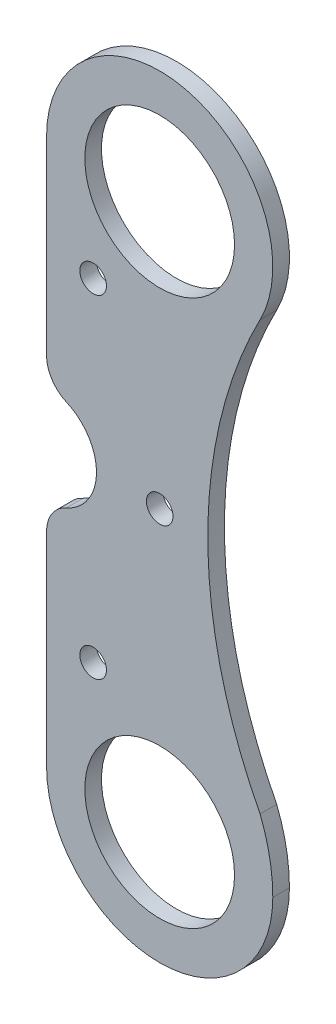
SolidWorks part; units mm, degrees
material "6061 Alloy"
ref_plane "Front Plane" through (0, 0, 0) normal (0, 0, 1) x (1, 0, 0)
ref_plane "Top Plane" through (0, 0, 0) normal (0, 1, 0) x (1, 0, 0)
ref_plane "Right Plane" through (0, 0, 0) normal (1, 0, 0) x (0, 0, -1)
sketch "Sketch1" plane through (0, 0, 0) normal (0, 0, 1) x (1, 0, 0)
  line L0 (0, 0) -> (0, -101.6) construction
  line L1 (21.59, -120.5575) -> (-21.59, -120.5575) construction
  line L2 (-8.89, 25.4) -> (8.89, 25.4)
  line L3 (-21.59, 12.7) -> (-21.59, -117.7751)
  line L5 (21.59, 12.7) -> (21.59, -117.7751)
  line L9 (-23.3829, -122.6853) -> (-33.2033, -134.3394)
  line L10 (-36.322, 25.4) -> (20.828, 25.4) construction
  line L11 (-36.322, 25.4) -> (-36.322, -203.2) construction
  line L12 (-36.322, -203.2) -> (20.828, -203.2) construction
  line L13 (20.828, 25.4) -> (20.828, -203.2) construction
  line L15 (-7.9527, -155.6168) -> (19.7971, -122.6853)
  line L16 (-32.4392, -143.2871) -> (-16.9004, -156.3809)
  circle A0 centre (0, 0) radius 38.1 construction
  circle A1 centre (0, -101.6) radius 38.1 construction
  circle A2 centre (0, 0) radius 14.2875
  circle A3 centre (0, -101.6) radius 14.2875
  arc A6 (8.89, 25.4) -> (21.59, 12.7) centre (8.89, 12.7) cw
  arc A7 (-8.89, 25.4) -> (-21.59, 12.7) centre (-8.89, 12.7) ccw
  circle A10 centre (-18.5321, -142.5501) radius 2.54
  arc A13 (-23.3829, -122.6853) -> (-21.59, -117.7751) centre (-29.21, -117.7751) ccw
  arc A14 (19.7971, -122.6853) -> (21.59, -117.7751) centre (13.97, -117.7751) ccw
  arc A15 (-16.9004, -156.3809) -> (-7.9527, -155.6168) centre (-12.8086, -151.525) ccw
  arc A16 (-33.2033, -134.3394) -> (-32.4392, -143.2871) centre (-28.3474, -138.4312) ccw
  circle A17 centre (0, -50.8) radius 2.54
  point P13 (-192.705, 39.2708)
  point P20 (21.59, 25.4)
  point P23 (-21.59, 25.4)
  point P31 (-36.322, -138.0404)
  dimension "D2" = 76.2
  dimension "D3" = 76.2
  dimension "D4" = 28.575
  dimension "D5" = 28.575
  dimension "D10" = 228.6
  dimension "D11" = 36.322
  dimension "D13" = 5.08
  dimension "D19" = 6.35
  dimension "D20" = 7.62
  dimension "D21" = 12.7
  dimension "D22" = 5.08
  dimension "D1" = 101.6
  dimension "D6" = 43.18
  dimension "D7" = 21.59
  dimension "D8" = 25.4
  dimension "D9" = 57.15
  dimension "D12" = 25.4
  dimension "D14" = 33.02
  dimension "D15" = 16.51
  dimension "D16" = 21.59
  dimension "D17" = 9.525
  dimension "D18" = 18.9575
extrude "Boss-Extrude1" add sketch "Sketch1" along normal blind 3.175
sketch "Sketch2" plane through (0, 0, 0) normal (0, 0, 1) x (1, 0, 0)
  line L0 (-21.59, -41.275) -> (-21.59, -60.325)
  line L1 (0, 0) -> (0, -101.6) construction
  line L4 (21.59, -117.7751) -> (21.59, 12.7) construction
  line L5 (-21.59, -50.8) -> (97.79, -50.8) construction
  line L6 (-21.59, 12.7) -> (-21.59, -117.7751) construction
  line L7 (0, 0) -> (-39.9512, 0) construction
  line L9 (16.51, -115.5122) -> (-17.5013, -155.8745)
  line L10 (-32.4392, -143.2871) -> (-16.9004, -156.3809) construction
  line L11 (-7.9527, -155.6168) -> (19.7971, -122.6853) construction
  line L13 (27.94, -121.6567) -> (-7.6203, -163.8572)
  line L14 (-7.6203, -163.8572) -> (-17.5013, -155.8745)
  line L15 (27.94, -121.6567) -> (27.94, 0)
  line L16 (27.94, 0) -> (21.59, 0)
  arc A1 (19.1591, -91.6472) -> (19.1591, -9.9528) centre (97.79, -50.8) cw
  arc A2 (-21.59, -60.325) -> (-21.59, -41.275) centre (-21.59, -50.8) ccw
  arc A3 (21.59, 0) -> (19.1591, -9.9528) centre (0, 0) cw
  arc A4 (21.59, -101.6) -> (19.1591, -91.6472) centre (0, -101.6) ccw
  arc A5 (21.59, -101.6) -> (16.51, -115.5122) centre (0, -101.6) cw
  dimension "D2" = 12.7
  dimension "D3" = 50.8
  dimension "D4" = 6.35
  dimension "D1" = 76.2
  dimension "D5" = 19.05
extrude "Cut-Extrude1" cut sketch "Sketch2" along normal through all contours A1 A3 L16 L15 L13 L14 L9 A5 A4 | L0 A2
sketch "Sketch3" plane through (0, 0, 3.175) normal (0, 0, 1) x (1, 0, 0)
  line L0 (-27.3514, -127.3948) -> (-36.0255, -137.6886)
  line L3 (-27.3514, -127.3948) -> (-7.5576, -144.074)
  line L4 (-23.3829, -122.6853) -> (-33.2033, -134.3394) construction
  line L5 (16.51, -115.5122) -> (-17.5013, -155.8745) construction
  line L7 (-35.4064, -144.9387) -> (-24.4031, -154.2106)
  line L8 (-23.3829, -122.6853) -> (-33.2033, -134.3394) construction
  line L9 (-7.5576, -144.074) -> (-15.4554, -153.4465)
  line L10 (-32.4392, -143.2871) -> (-17.5013, -155.8745) construction
  circle A2 centre (-18.5321, -142.5501) radius 2.54
  circle A3 centre (-18.5321, -142.5501) radius 2.54 construction
  arc A5 (-36.0255, -137.6886) -> (-35.4064, -144.9387) centre (-32.0909, -141.0041) ccw
  arc A6 (-24.4031, -154.2106) -> (-15.4554, -153.4465) centre (-20.3113, -149.3547) ccw
  dimension "D2" = 6.35
  dimension "D3" = 5.1453
  dimension "D1" = 3.175
fillet "Fillet3" radius 6.35 2 edges at (-21.59, -60.325, 1.5875) (-21.59, -41.275, 1.5875)
extrude "Boss-Extrude3" add sketch "Sketch3" against normal blind 3.175
sketch "Sketch6" plane through (0, 0, 3.175) normal (0, 0, 1) x (1, 0, 0)
  line L0 (-35.4064, -144.9387) -> (-63.6204, -121.1641)
  line L1 (-63.6204, -121.1641) -> (-51.345, -106.5965)
  line L2 (-51.345, -106.5965) -> (-27.0656, -127.0555)
  line L4 (-35.4064, -144.9387) -> (-24.4031, -154.2106) construction
  line L5 (-23.3829, -122.6853) -> (-36.0255, -137.6886) construction
  line L6 (-35.4064, -144.9387) -> (-27.0656, -127.0555)
  circle A0 centre (-52.6268, -117.9721) radius 2.54
  dimension "D4" = 5.08
  dimension "D1" = 31.75
  dimension "D2" = 9.525
  dimension "1" = 19.05
  dimension "D3" = 6.35
extrude "Boss-Extrude4" add sketch "Sketch6" against normal blind 3.175
fillet "Fillet2" radius 6.35 3 edges at (-63.6204, -121.1641, 1.5875) (-51.345, -106.5965, 1.5875) (-27.0656, -127.0555, 1.5875)
sketch "Sketch7" plane through (0, 0, 3.175) normal (0, 0, 1) x (1, 0, 0)
  line L0 (-21.59, 12.7) -> (-21.59, -36.2503) construction
  line L1 (21.59, 0) -> (21.59, 12.7) construction
  line L2 (-21.59, 0) -> (21.59, 0) construction
  line L3 (-21.59, 0) -> (-21.59, 31.75)
  line L4 (-21.59, 31.75) -> (21.59, 31.75)
  line L5 (21.59, 31.75) -> (21.59, 0)
  line L6 (8.89, 25.4) -> (-8.89, 25.4) construction
  arc A0 (-21.59, 0) -> (21.59, 0) centre (0, 0) cw
  dimension "D1" = 6.35
extrude "Cut-Extrude2" cut sketch "Sketch7" against normal through all
sketch "Sketch10" plane through (0, 0, 3.175) normal (0, 0, 1) x (1, 0, 0)
  line L0 (16.51, -115.5122) -> (-17.5013, -155.8745) construction
  line L1 (-18.1519, -155.3263) -> (-17.3615, -157.512)
  line L2 (-17.3615, -157.512) -> (-14.3757, -156.4323)
  line L3 (-14.3757, -156.4323) -> (-15.4554, -153.4465)
  line L5 (-18.1519, -155.3263) -> (-17.5013, -155.8745) construction
  circle A0 centre (-20.3113, -149.3547) radius 6.35 construction
  arc A1 (-24.4031, -154.2106) -> (-18.1519, -155.3263) centre (-20.3113, -149.3547) ccw construction
  arc A2 (-18.1519, -155.3263) -> (-15.4554, -153.4465) centre (-20.3113, -149.3547) ccw
  dimension "D1" = 3.175
  dimension "D2" = 30
extrude "Cut-Extrude3" cut sketch "Sketch10" against normal through all
sketch "Sketch12" plane through (0, 0, 3.175) normal (0, 0, 1) x (1, 0, 0)
  line L0 (-21.59, -65.3497) -> (-21.59, -117.7751) construction
  line L1 (-21.59, -101.6) -> (-72.39, -101.6)
  line L2 (-72.39, -101.6) -> (-72.39, -165.1)
  line L3 (-72.39, -165.1) -> (16.51, -165.1)
  line L4 (16.51, -165.1) -> (16.51, -115.5122)
  arc A2 (16.51, -115.5122) -> (-21.59, -101.6) centre (0, -101.6) cw
  dimension "D1" = 63.5
  dimension "D2" = 88.9
extrude "Cut-Extrude4" cut sketch "Sketch12" against normal through all
sketch "Sketch13" plane through (0, 0, 3.175) normal (0, 0, 1) x (1, 0, 0)
  line L0 (-21.59, -101.6) -> (-21.59, -104.2391)
  line L1 (21.59, -101.6) -> (21.59, -104.2391)
  line L2 (-21.59, -101.6) -> (-7.35, -118.3664)
  line L3 (-7.35, -118.3664) -> (6.6629, -118.3664)
  line L4 (6.6629, -118.3664) -> (21.59, -101.6)
  arc A0 (-21.59, -104.2391) -> (21.59, -104.2391) centre (0, -104.2391) ccw
  arc A1 (-21.59, -101.6) -> (19.1591, -91.6472) centre (0, -101.6) ccw construction
  dimension "D1" = 2.6391
extrude "Boss-Extrude7" add sketch "Sketch13" against normal through all contours A0 L1 L4 L3 L2 L0
sketch "Sketch14" plane through (0, 0, 3.175) normal (0, 0, 1) x (1, 0, 0)
  circle A0 centre (0, -101.6) radius 14.2875
  circle A1 centre (0, -101.6) radius 14.2875 construction
extrude "Boss-Extrude8" add sketch "Sketch14" against normal through all
sketch "Sketch15" plane through (0, 0, 3.175) normal (0, 0, 1) x (1, 0, 0)
  circle A0 centre (0, -104.2391) radius 14.2875
  arc A1 (-21.59, -104.2391) -> (21.59, -104.2391) centre (0, -104.2391) ccw construction
  dimension "D1" = 28.575
extrude "Cut-Extrude5" cut sketch "Sketch15" against normal through all
sketch "Sketch16" plane through (0, 0, 3.175) normal (0, 0, 1) x (1, 0, 0)
  line L0 (21.59, -104.2391) -> (21.59, -94.3525) construction
  line L1 (19.1591, -91.6472) -> (21.59, -91.6472)
  line L2 (21.59, -91.6472) -> (21.59, -104.2391)
  arc A0 (19.1591, -91.6472) -> (21.59, -104.2391) centre (-12.2375, -104.2391) cw
extrude "Cut-Extrude6" cut sketch "Sketch16" against normal through all
sketch "Sketch17" plane through (0, 0, 0) normal (0, 0, -1) x (-1, 0, 0)
  circle A0 centre (12.7, -19.05) radius 2.54
  circle A1 centre (12.7, -82.55) radius 2.54
  circle A2 centre (0, -50.8) radius 2.54 construction
  circle A3 centre (0, -50.8) radius 2.54
  dimension "D1" = 12.7
  dimension "D2" = 12.7
  dimension "D3" = 31.75
  dimension "D4" = 31.75
extrude "Cut-Extrude7" cut sketch "Sketch17" against normal through all
